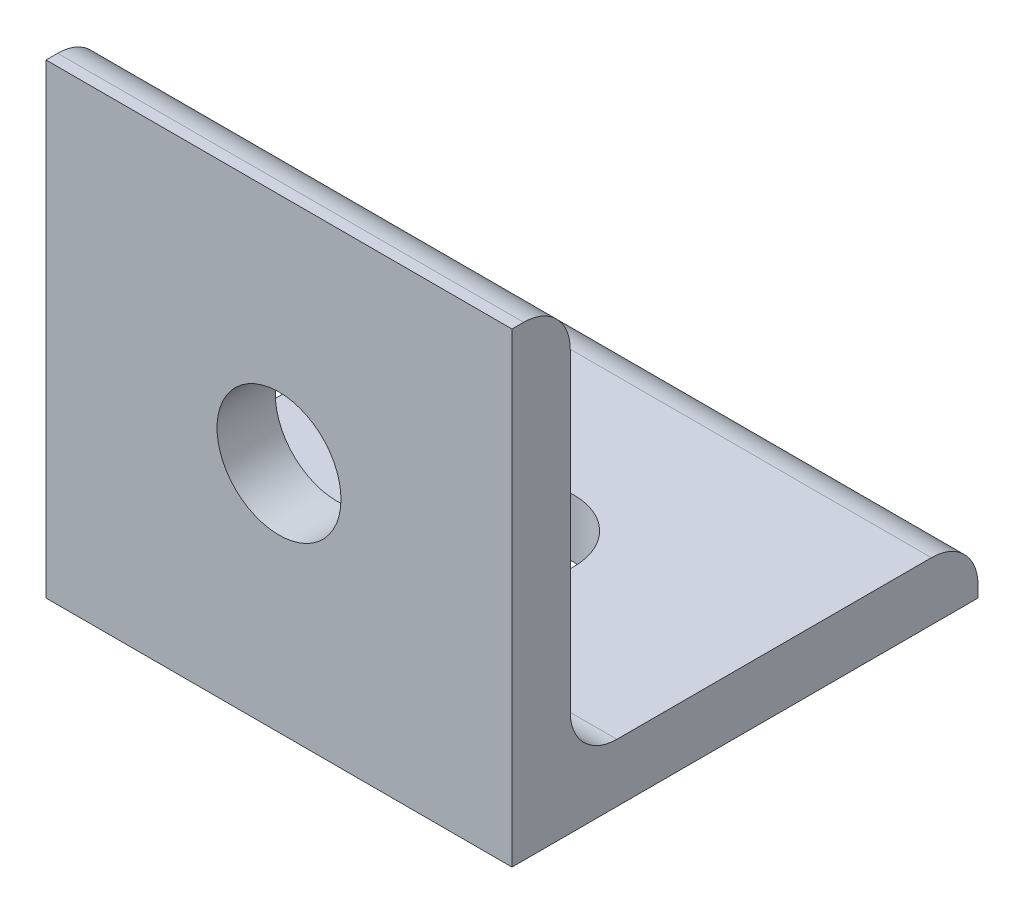
SolidWorks part; units mm, degrees
ref_plane "Front" through (0, 0, 0) normal (0, 0, 1) x (1, 0, 0)
ref_plane "Top" through (0, 0, 0) normal (0, 1, 0) x (1, 0, 0)
ref_plane "Right" through (0, 0, 0) normal (1, 0, 0) x (0, 0, -1)
sketch "Sketch1" plane through (0, 0, 0) normal (1, 0, 0) x (0, 0, -1)
  line L0 (0, 0) -> (0, 25.4)
  line L1 (0, 25.4) -> (3.175, 25.4)
  line L2 (3.175, 25.4) -> (3.175, 3.175)
  line L3 (3.175, 3.175) -> (25.4, 3.175)
  line L4 (25.4, 3.175) -> (25.4, 0)
  line L5 (25.4, 0) -> (0, 0)
  dimension "D1" = 3.175
  dimension "D2" = 25.4
extrude "Extrude1" add sketch "Sketch1" along normal mid plane 25.4
hole_wizard "1/4 Clearance Hole1" positions "Sketch3" profile "Sketch2" hole size "1/4" standard "Ansi Inch" end condition up to next
sketch "Sketch3" plane through (0, 0, 0) normal (0, 0, 1) x (1, 0, 0)
  line L0 (-12.7, 25.4) -> (12.7, 0) construction
  point P0 (0, 12.7)
sketch "Sketch2" plane through (0, 12.7, 0) normal (1, 0, 0) x (0, -1, 0)
  line L0 (0, 0) -> (0, 3.175)
  line L1 (0, 3.175) -> (3.3782, 3.175)
  line L2 (3.3782, 3.175) -> (3.3782, 0)
  line L5 (3.3782, 0) -> (0, 0)
  line L11 (0, -6.35) -> (0, 107.95) construction
  dimension "Thru Hole Dia." = 6.7564
  dimension "Thru Hole Depth" = 3.175
hole_wizard "1/4 Clearance Hole2" positions "Sketch5" profile "Sketch4" hole size "1/4" standard "Ansi Inch" end condition up to next
sketch "Sketch5" plane through (0, 0, 0) normal (0, -1, 0) x (1, 0, 0)
  line L0 (-12.7, 0) -> (12.7, -25.4) construction
  point P0 (0, -12.7)
sketch "Sketch4" plane through (0, 0, -12.7) normal (1, 0, 0) x (0, 0, -1)
  line L0 (0, 0) -> (0, 3.175)
  line L1 (0, 3.175) -> (3.3782, 3.175)
  line L2 (3.3782, 3.175) -> (3.3782, 0)
  line L5 (3.3782, 0) -> (0, 0)
  line L11 (0, -6.35) -> (0, 107.95) construction
  dimension "Thru Hole Dia." = 6.7564
  dimension "Thru Hole Depth" = 3.175
fillet "Fillet1" radius 2.54 3 edges at (0, 3.175, -3.175) (0, 3.175, -25.4) (0, 25.4, -3.175)
